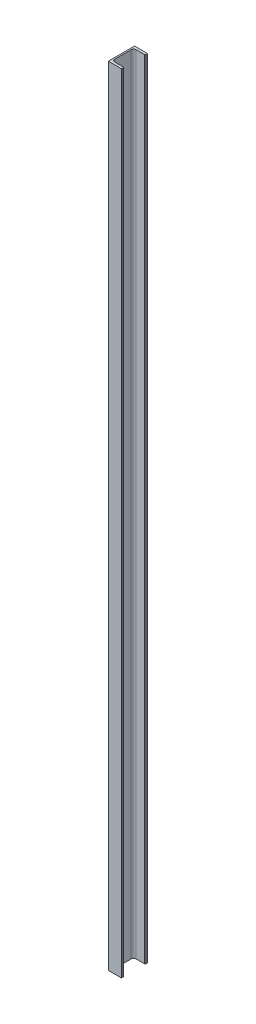
SolidWorks part; units mm, degrees
material "1.1181 (C35E)"
ref_plane "Спереди" through (0, 0, 0) normal (0, 0, 1) x (1, 0, 0)
ref_plane "Сверху" through (0, 0, 0) normal (0, 1, 0) x (1, 0, 0)
ref_plane "Справа" through (0, 0, 0) normal (1, 0, 0) x (0, 0, -1)
sketch "Эскиз1" plane through (0, 0, 0) normal (0, 1, 0) x (1, 0, 0)
  line L0 (20, 35.1) -> (20, 40)
  line L5 (-20, -40) -> (20, -40)
  line L6 (-20, -40) -> (-20, 40)
  line L11 (-20, 40) -> (20, 40)
  line L12 (20, -40) -> (20, -35.1)
  line L13 (-20, -40) -> (20, 40) construction
  line L14 (-20, 40) -> (20, -40) construction
  line L15 (17.5, 32.6) -> (-8, 32.6)
  line L17 (17.5, -32.6) -> (-8, -32.6)
  line L18 (-15.5, 25.1) -> (-15.5, -25.1)
  arc A0 (-15.5, -25.1) -> (-8, -32.6) centre (-8, -25.1) ccw
  arc A1 (-15.5, 25.1) -> (-8, 32.6) centre (-8, 25.1) cw
  arc A2 (20, -35.1) -> (17.5, -32.6) centre (17.5, -35.1) ccw
  arc A3 (20, 35.1) -> (17.5, 32.6) centre (17.5, 35.1) cw
  point P0 (0, 0)
  point P18 (20, 32.6)
  dimension "D6" = 7.5
  dimension "D7" = 2.5
  dimension "D1" = 80
  dimension "D2" = 40
  dimension "D3" = 7.4
  dimension "D4" = 7.4
  dimension "D5" = 4.5
extrude "Бобышка-Вытянуть1" add sketch "Эскиз1" along normal blind 2400
